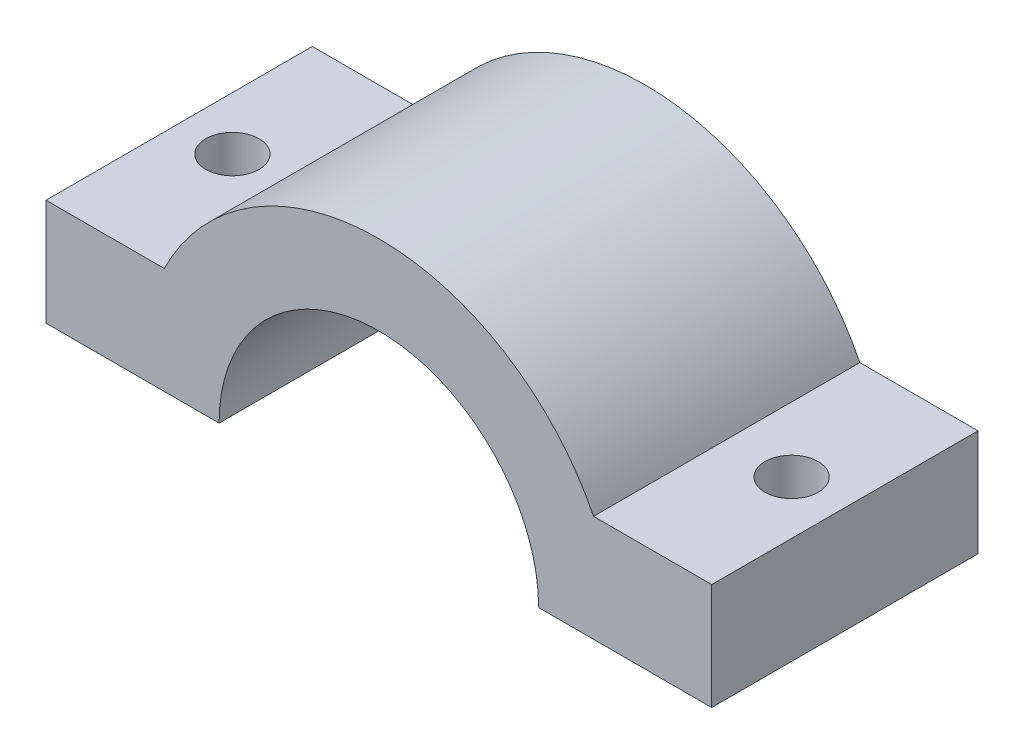
SolidWorks part; units mm, degrees
ref_plane "Alzado" through (0, 0, 0) normal (0, 0, 1) x (1, 0, 0)
ref_plane "Planta" through (0, 0, 0) normal (0, 1, 0) x (1, 0, 0)
ref_plane "Vista lateral" through (0, 0, 0) normal (1, 0, 0) x (0, 0, -1)
sketch "Croquis1" plane through (0, 0, 0) normal (0, 0, 1) x (1, 0, 0)
  line L1 (12.5, -2) -> (6, -2)
  line L2 (12.5, -2) -> (12.5, 2)
  line L3 (12.5, 2) -> (8.0623, 2)
  line L4 (-12.5, -2) -> (-12.5, 2)
  line L7 (-6, -2) -> (-12.5, -2)
  line L10 (-8.0623, 2) -> (-12.5, 2)
  arc A0 (6, -2) -> (-6, -2) centre (0, -2) ccw
  arc A2 (8.0623, 2) -> (-8.0623, 2) centre (0, -2) ccw
  point P0 (0, 0)
extrude "Saliente-Extruir1" add sketch "Croquis1" along normal blind 10
sketch "Croquis2" plane through (0, 2, 0) normal (0, 1, 0) x (1, 0, 0)
  circle A0 centre (10.5, -5) radius 1
extrude "Cortar-Extruir1" cut sketch "Croquis2" against normal blind 10
mirror "Simetría1" about plane through (0, 0, 0) normal (1, 0, 0) of "Cortar-Extruir1"
